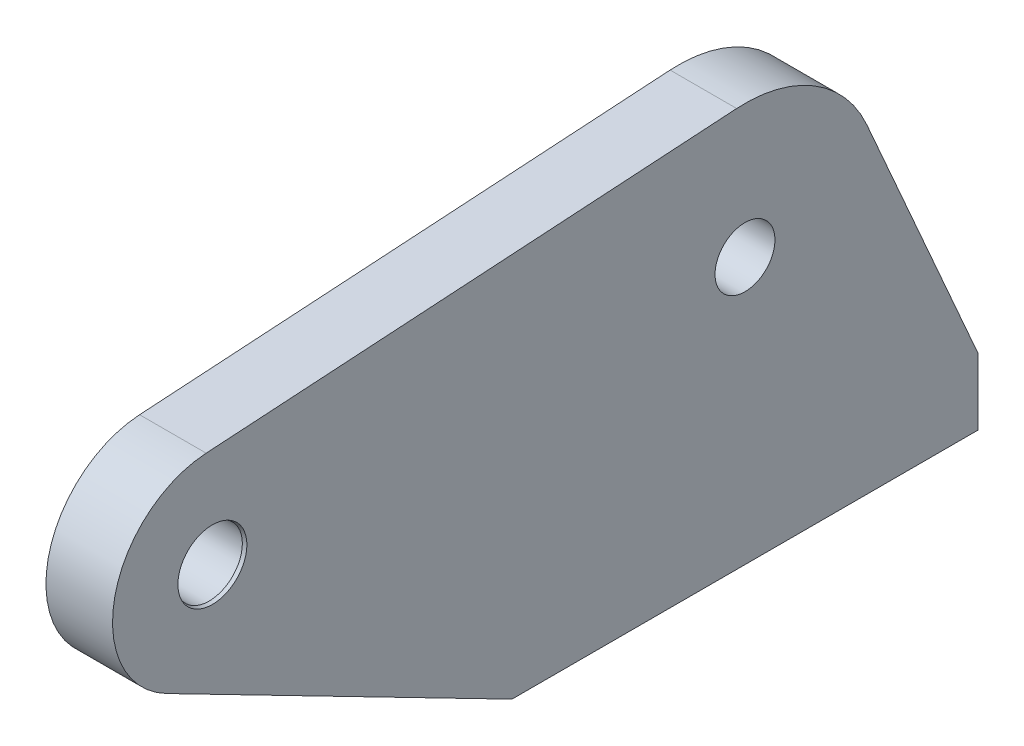
SolidWorks part; units mm, degrees
material "ALUMINIUM,  6082-T6"
ref_plane "Front Plane" through (0, 0, 0) normal (0, 0, 1) x (1, 0, 0)
ref_plane "Top Plane" through (0, 0, 0) normal (0, 1, 0) x (1, 0, 0)
ref_plane "Right Plane" through (0, 0, 0) normal (1, 0, 0) x (0, 0, -1)
sketch "Sketch1" plane through (0, 0, 0) normal (1, 0, 0) x (0, 0, -1)
  line L0 (-18.3152, 8.0344) -> (-35, -30)
  line L1 (-35, -40) -> (35, -40)
  line L2 (35, -30) -> (18.3152, 8.0344)
  line L3 (0, 0) -> (0, -40) construction
  line L4 (-35, -30) -> (-35, -40)
  line L7 (35, -30) -> (35, -40)
  arc A0 (18.3152, 8.0344) -> (-18.3152, 8.0344) centre (0, 0) ccw
  dimension "D1" = 20
  dimension "D2" = 40
  dimension "D3" = 10
  dimension "D4" = 70
extrude "Boss-Extrude1" add sketch "Sketch1" along normal mid plane 10
hole_wizard "Ø9.0 (9) Diameter Hole1" positions "Sketch3" profile "Sketch4" hole size "Ø9.0" standard "ISO" end condition through all
sketch "Sketch3" plane through (5, 0, 0) normal (1, 0, 0) x (0, 0, -1)
  point P0 (0, 0)
sketch "Sketch4" plane through (5, 0, 0) normal (0, 1, 0) x (0, 0, -1)
  line L0 (0, 0) -> (0, 10)
  line L1 (0, 10) -> (4.5, 10)
  line L2 (4.5, 10) -> (4.5, 0)
  line L5 (4.5, 0) -> (0, 0)
  line L11 (0, -6.35) -> (0, 107.95) construction
  dimension "Thru Hole Dia." = 9
  dimension "Thru Hole Depth" = 10
hole_wizard "M4 Tapped Hole1" positions "Sketch5" profile "Sketch6" tap size "M4" standard "ISO"
sketch "Sketch5" plane through (0, -40, 0) normal (0, -1, 0) x (-1, 0, 0)
  line L0 (0, -25) -> (0, -10) construction
  line L1 (0, -10) -> (0, 10) construction
  line L2 (0, 10) -> (0, 25) construction
  line L3 (-5, 35) -> (5, 35) construction
  point P0 (0, -25)
  point P2 (0, -10)
  point P4 (0, 10)
  point P6 (0, 25)
  dimension "D1" = 15
  dimension "D2" = 10
  dimension "D3" = 20
sketch "Sketch6" plane through (0, -40, 25) normal (1, 0, 0) x (0, 0, -1)
  line L0 (0, 0) -> (0, 12.4914)
  line L1 (0, 12.4914) -> (1.65, 11.5)
  line L2 (1.65, 11.5) -> (1.65, 0)
  line L5 (1.65, 0) -> (0, 0)
  line L10 (0, 12.4914) -> (-1.65, 11.5) construction
  line L11 (0, -6.35) -> (0, 107.95) construction
  dimension "Tap Drill Dia." = 3.3
  dimension "Tap Drill Depth" = 11.5
  dimension "Drill Angle" = 118
cosmetic thread "Hole Thread1" parameters "D1"=8, "D2"=4
cosmetic thread "Hole Thread2" parameters "D1"=8, "D2"=4
cosmetic thread "Hole Thread3" parameters "D1"=8, "D2"=4
cosmetic thread "Hole Thread4" parameters "D1"=8, "D2"=4
sketch "Sketch7" plane through (5, 0, 0) normal (1, 0, 0) x (0, 0, -1)
  line L0 (-80.9375, 14.9707) -> (-1.25, 19.9609)
  line L1 (-86.8581, -13.3404) -> (-35, -40)
  line L2 (-18.3152, 8.0344) -> (-35, -30) construction
  line L3 (-35, -30) -> (-35, -40) construction
  line L4 (-18.3152, 8.0344) -> (-35, -30)
  line L5 (-35, -30) -> (-35, -40)
  arc A0 (-80.9375, 14.9707) -> (-86.8581, -13.3404) centre (-80, 0) ccw
  arc A1 (18.3152, 8.0344) -> (-18.3152, 8.0344) centre (0, 0) ccw construction
  arc A2 (-1.25, 19.9609) -> (-18.3152, 8.0344) centre (0, 0) ccw
  dimension "D1" = 30
  dimension "D2" = 80
extrude "Boss-Extrude2" add sketch "Sketch7" against normal blind 10
sketch "Sketch8" plane through (5, 0, 0) normal (1, 0, 0) x (0, 0, -1)
  circle A0 centre (-80, 0) radius 5
  arc A1 (-80.9375, 14.9707) -> (-86.8581, -13.3404) centre (-80, 0) ccw construction
  dimension "D1" = 10
extrude "Cut-Extrude1" cut sketch "Sketch8" against normal blind 10
chamfer "Chamfer1" distance 0.5 angle 20 2 edges at (5, 0, 75) (-5, 0, 75)
